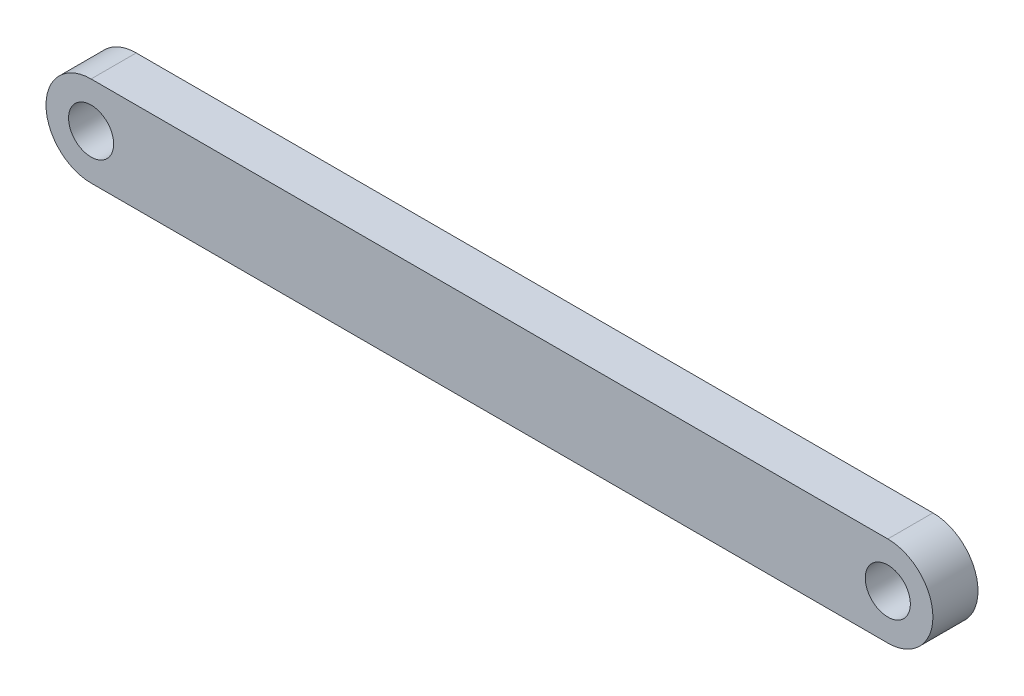
SolidWorks part; units mm, degrees
ref_plane "Front Plane" through (0, 0, 0) normal (0, 0, 1) x (1, 0, 0)
ref_plane "Top Plane" through (0, 0, 0) normal (0, 1, 0) x (1, 0, 0)
ref_plane "Right Plane" through (0, 0, 0) normal (1, 0, 0) x (0, 0, -1)
sketch "Sketch1" plane through (0, 0, 0) normal (0, 0, 1) x (1, 0, 0)
  line L0 (0, 0) -> (-53, 0)
  dimension "D1" = 53
sketch "Sketch2" plane through (0, 0, 0) normal (0, 0, 1) x (1, 0, 0)
  line L0 (-53, 3) -> (0, 3)
  line L1 (-53, -3) -> (0, -3)
  circle A0 centre (-53, 0) radius 1.5
  circle A1 centre (0, 0) radius 1.5
  arc A2 (-53, 3) -> (-53, -3) centre (-53, 0) ccw
  arc A3 (0, -3) -> (0, 3) centre (0, 0) ccw
  dimension "D1" = 3
  dimension "D2" = 6
  dimension "D3" = 3
  dimension "D4" = 6
extrude "Boss-Extrude1" add sketch "Sketch2" along normal blind 3
